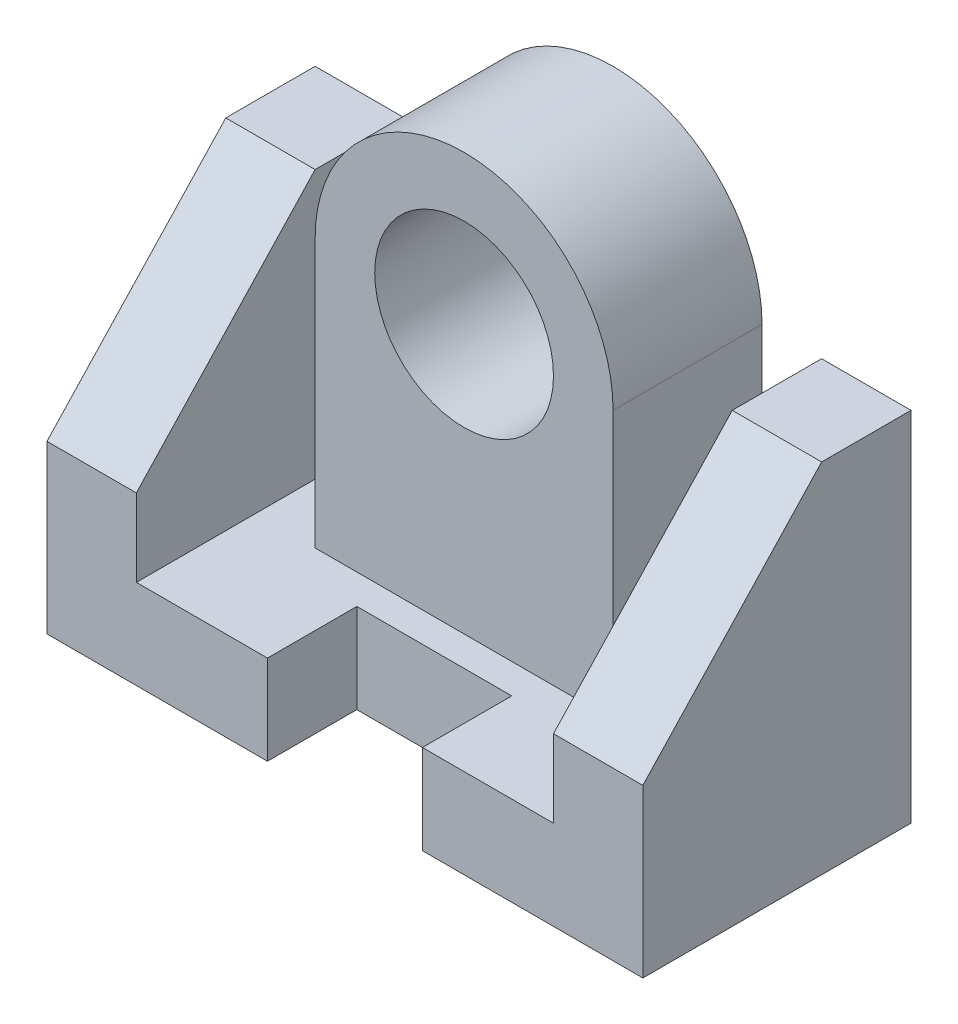
SolidWorks part; units mm, degrees
ref_plane "Front Plane" through (0, 0, 0) normal (0, 0, 1) x (1, 0, 0)
ref_plane "Top Plane" through (0, 0, 0) normal (0, 1, 0) x (1, 0, 0)
ref_plane "Right Plane" through (0, 0, 0) normal (1, 0, 0) x (0, 0, -1)
sketch "Sketch1" plane through (0, 0, 0) normal (0, 0, 1) x (1, 0, 0)
  line L0 (0, 0) -> (0, 60) construction
  line L1 (-50, 0) -> (-50, 60)
  line L2 (-50, 60) -> (-35, 60)
  line L3 (-35, 60) -> (-35, 15)
  line L4 (-35, 15) -> (35, 15)
  line L5 (35, 15) -> (35, 60)
  line L6 (35, 60) -> (50, 60)
  line L7 (50, 60) -> (50, 0)
  line L8 (50, 0) -> (-50, 0)
  dimension "D1" = 100
  dimension "D2" = 60
  dimension "D3" = 15
  dimension "D4" = 15
extrude "Boss-Extrude1" add sketch "Sketch1" along normal blind 45
sketch "Sketch2" plane through (50, 0, 0) normal (1, 0, 0) x (0, 0, -1)
  line L0 (-15, 60) -> (-45, 60)
  line L1 (-45, 60) -> (0, 60) construction
  line L2 (-45, 60) -> (-45, 28)
  line L3 (-45, 0) -> (-45, 60) construction
  line L4 (-45, 28) -> (-15, 60)
  line L5 (0, 0) -> (0, 60) construction
  line L6 (-45, 0) -> (0, 0) construction
  dimension "D1" = 15
  dimension "D2" = 28
extrude "Cut-Extrude1" cut sketch "Sketch2" against normal through all
sketch "Sketch3" plane through (0, 15, 0) normal (0, 1, 0) x (1, 0, 0)
  line L0 (0, 0) -> (0, -45) construction
  line L1 (35, -45) -> (-35, -45) construction
  line L3 (-13, -30) -> (13, -30)
  line L4 (13, -30) -> (13, -45)
  line L5 (13, -45) -> (-13, -45)
  line L6 (-13, -45) -> (-13, -30)
  dimension "D1" = 26
  dimension "D2" = 15
extrude "Cut-Extrude2" cut sketch "Sketch3" against normal through all
sketch "Sketch4" plane through (0, 0, 0) normal (0, 0, -1) x (-1, 0, 0)
  line L0 (0, 0) -> (0, 85) construction
  line L1 (25, 15) -> (25, 60)
  line L2 (-35, 15) -> (35, 15) construction
  line L3 (-25, 60) -> (-25, 15)
  line L4 (-25, 15) -> (25, 15)
  arc A0 (25, 60) -> (-25, 60) centre (0, 60) ccw
  dimension "D1" = 25
  dimension "D2" = 45
extrude "Boss-Extrude2" add sketch "Sketch4" against normal blind 25
sketch "Sketch5" plane through (0, 0, 25) normal (0, 0, 1) x (1, 0, 0)
  circle A0 centre (0, 60) radius 15
  arc A1 (25, 60) -> (-25, 60) centre (0, 60) ccw construction
  dimension "D1" = 30
extrude "Cut-Extrude3" cut sketch "Sketch5" against normal through all
